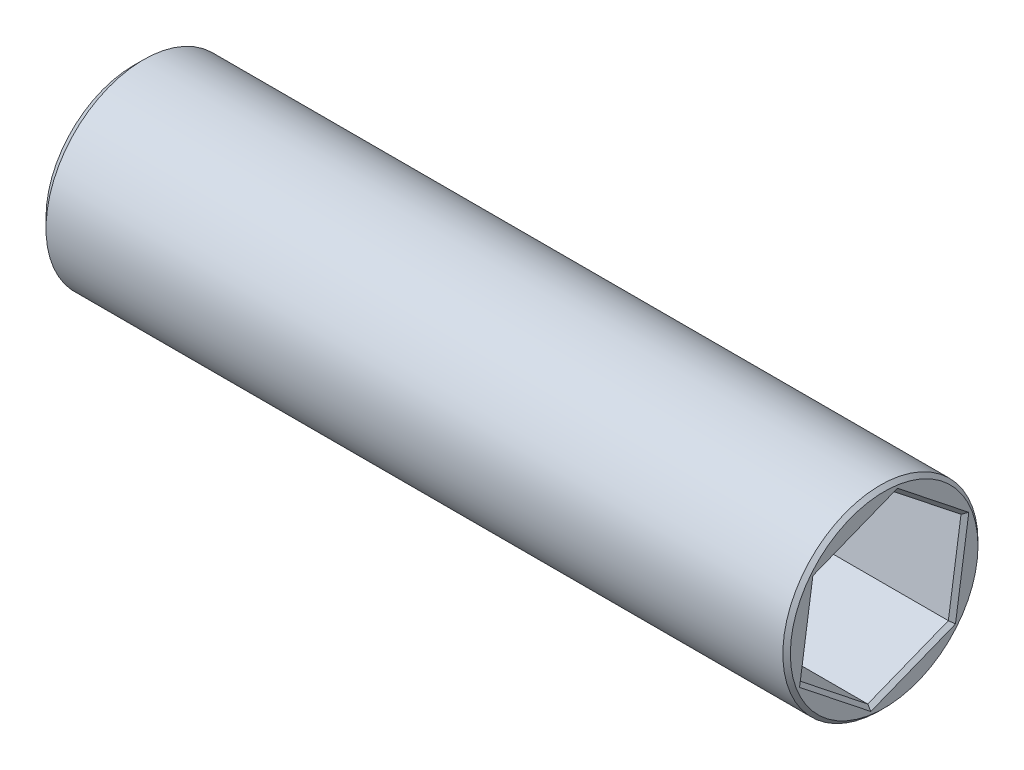
SolidWorks part; units mm, degrees
ref_plane "Front Plane" through (0, 0, 0) normal (0, 0, 1) x (1, 0, 0)
ref_plane "Top Plane" through (0, 0, 0) normal (0, 1, 0) x (1, 0, 0)
ref_plane "Right Plane" through (0, 0, 0) normal (1, 0, 0) x (0, 0, -1)
sketch "Sketch1" plane through (0, 0, 0) normal (1, 0, 0) x (0, 0, -1)
  circle A0 centre (0, 0) radius 3.9
  circle A1 centre (0, 0) radius 1.575
  dimension "D1" = 7.8
  dimension "D2" = 3.15
extrude "Boss-Extrude1" add sketch "Sketch1" along normal blind 30
sketch "Sketch2" plane through (30, 0, 0) normal (1, 0, 0) x (0, 0, -1)
  line L1 (0.5067, 3.4268) -> (-2.7144, 2.1522)
  line L2 (-2.7144, 2.1522) -> (-3.2211, -1.2746)
  line L3 (-3.2211, -1.2746) -> (-0.5067, -3.4268)
  line L4 (-0.5067, -3.4268) -> (2.7144, -2.1522)
  line L5 (2.7144, -2.1522) -> (3.2211, 1.2746)
  line L6 (3.2211, 1.2746) -> (0.5067, 3.4268)
  circle A0 centre (0, 0) radius 3 construction
  dimension "D1" = 6
extrude "Cut-Extrude1" cut sketch "Sketch2" against normal offset from surface (25 mm away) 5 up to face at (0, 0, -3.9)
chamfer "Chamfer1" distance 0.4 angle 45 2 edges at (0, 0, -1.575) (0, 0, -3.9)
chamfer "Chamfer2" distance 0.15 angle 45 7 edges at (30, 0, -3.9) (30, 2.7895, 1.1039) (30, 0.4388, 2.9677) (30, -2.3507, 1.8639) (30, -2.7895, -1.1039) (30, -0.4388, -2.9677) (30, 2.3507, -1.8639)
